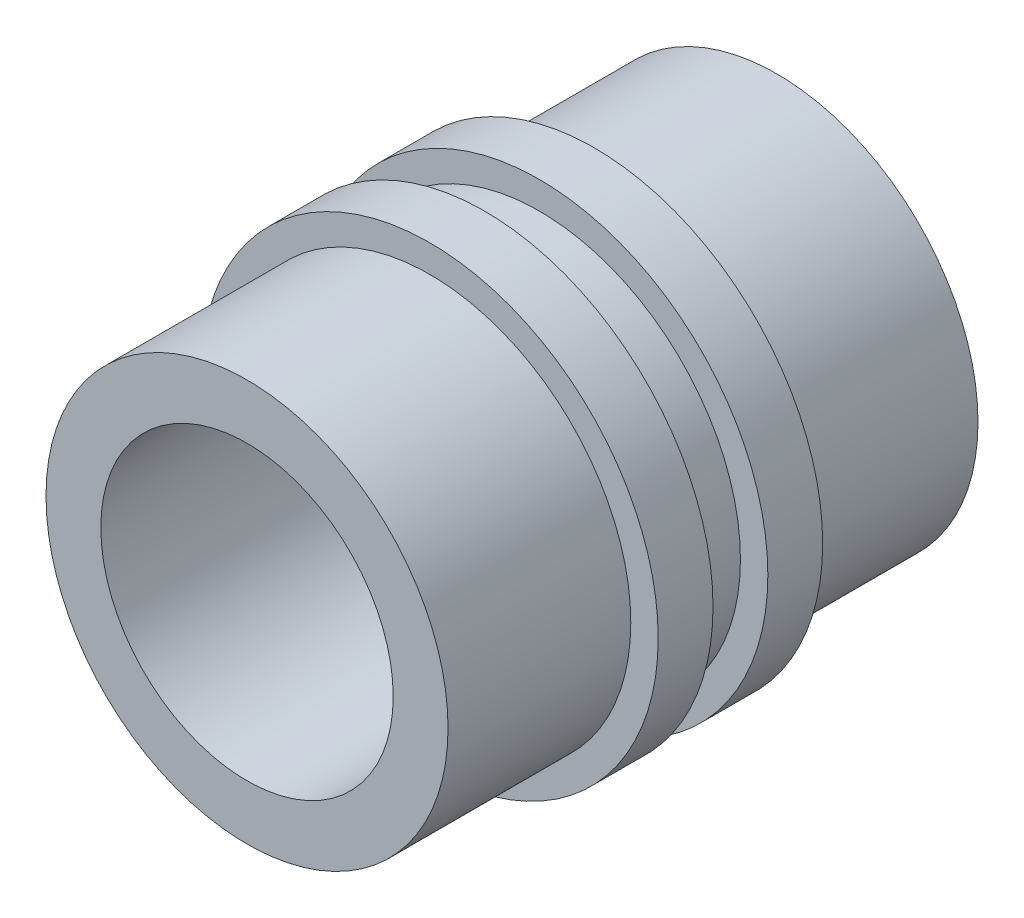
SolidWorks part; units mm, degrees
ref_plane "Plan de face" through (0, 0, 0) normal (0, 0, 1) x (1, 0, 0)
ref_plane "Plan de dessus" through (0, 0, 0) normal (0, 1, 0) x (1, 0, 0)
ref_plane "Plan de droite" through (0, 0, 0) normal (1, 0, 0) x (0, 0, -1)
sketch "Esquisse3" plane through (0, 0, 0) normal (0, 0, 1) x (1, 0, 0)
  circle A0 centre (0, 0) radius 15
  dimension "D1" = 30
extrude "Boss.-Extru.2" add sketch "Esquisse3" against normal blind 3.6
sketch "Esquisse4" plane through (0, 0, -3.6) normal (0, 0, -1) x (-1, 0, 0)
  circle A0 centre (0, 0) radius 13.2
  dimension "D1" = 26.4
extrude "Boss.-Extru.3" add sketch "Esquisse4" along normal blind 12
sketch "Esquisse5" plane through (0, 0, 0) normal (0, 0, 1) x (1, 0, 0)
  circle A0 centre (0, 0) radius 13.2
  dimension "D1" = 26.4
extrude "Boss.-Extru.4" add sketch "Esquisse5" along normal blind 3.6
sketch "Esquisse6" plane through (0, 0, 3.6) normal (0, 0, 1) x (1, 0, 0)
  circle A0 centre (0, 0) radius 15
extrude "Boss.-Extru.5" add sketch "Esquisse6" along normal blind 3.6
sketch "Esquisse7" plane through (0, 0, 7.2) normal (0, 0, 1) x (1, 0, 0)
  circle A0 centre (0, 0) radius 13.2
  dimension "D1" = 26.4
extrude "Boss.-Extru.6" add sketch "Esquisse7" along normal blind 12
sketch "Esquisse8" plane through (0, 0, 19.2) normal (0, 0, 1) x (1, 0, 0)
  circle A0 centre (0, 0) radius 9.6
  dimension "D1" = 19.2
extrude "Enlèv. mat.-Extru.2" cut sketch "Esquisse8" against normal blind 123
